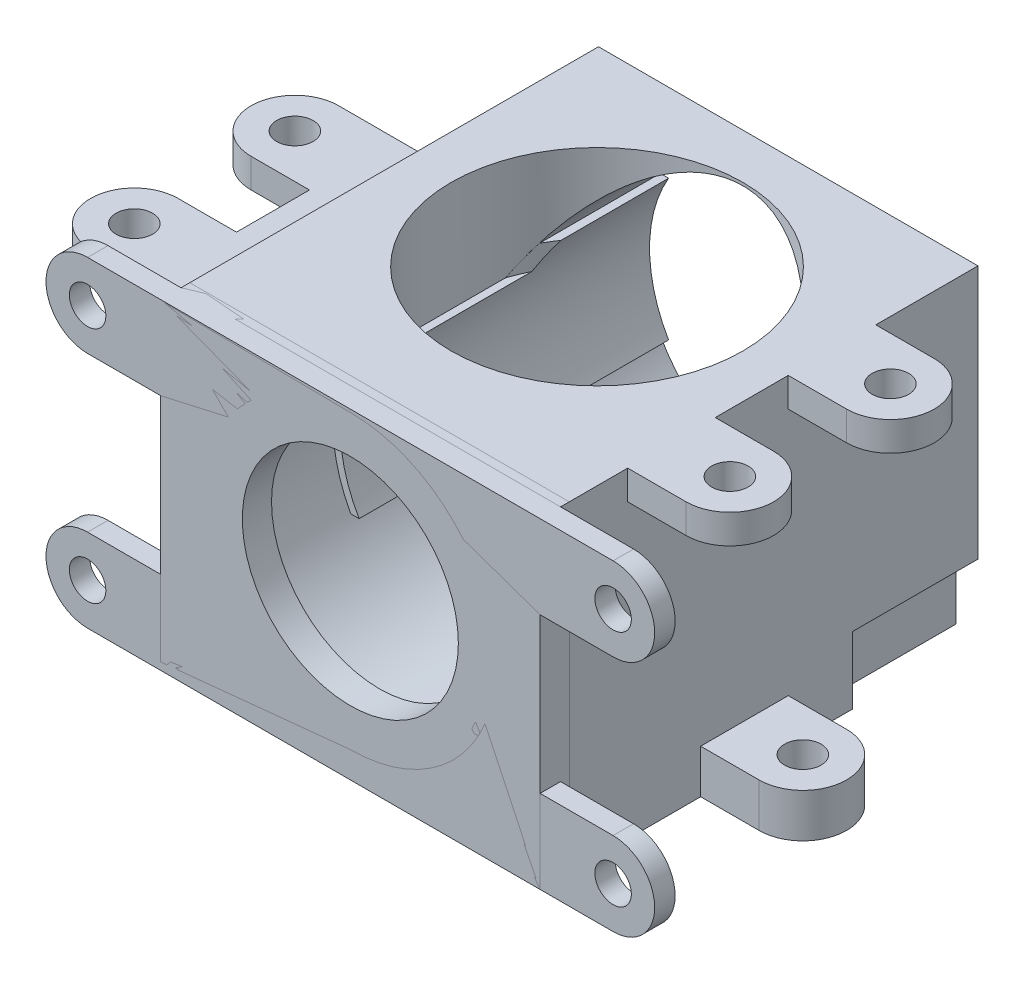
SolidWorks part; units mm, degrees
ref_plane "Front Plane" through (0, 0, 0) normal (0, 0, 1) x (1, 0, 0)
ref_plane "Top Plane" through (0, 0, 0) normal (0, 1, 0) x (1, 0, 0)
ref_plane "Right Plane" through (0, 0, 0) normal (1, 0, 0) x (0, 0, -1)
sketch "Sketch1" plane through (0, 0, 0) normal (0, 0, 1) x (1, 0, 0)
  line L1 (0, 0) -> (33.02, 0)
  line L2 (0, 0) -> (0, 27.94)
  line L3 (0, 27.94) -> (33.02, 27.94)
  line L4 (33.02, 0) -> (33.02, 27.94)
  dimension "D1" = 33.02
  dimension "D2" = 27.94
extrude "Boss-Extrude1" add sketch "Sketch1" along normal blind 38.1
sketch "Sketch2" plane through (0, 0, 38.1) normal (0, 0, 1) x (1, 0, 0)
  line L2 (0, 0) -> (33.02, 0) construction
  line L3 (33.02, 27.94) -> (0, 27.94) construction
  circle A1 centre (16.51, 14.986) radius 12.7
  point P10 (16.51, 0)
  dimension "D1" = 25.4
  dimension "D2" = 12.954
sketch "Sketch4" plane through (0, 27.94, 0) normal (0, 1, 0) x (1, 0, 0)
  line L0 (33.02, 0) -> (0, 0) construction
  line L1 (0, -38.1) -> (0, 0) construction
  circle A0 centre (16.51, -16.637) radius 12.7
  dimension "D1" = 25.4
  dimension "D2" = 16.637
  dimension "D3" = 16.51
extrude "Cut-Extrude3" cut sketch "Sketch4" against normal blind 14.224
ref_plane "Plane4" through (0, 3.81, 0) normal (0, -1, 0) x (-1, 0, 0)
sketch "Sketch3" plane through (0, 3.81, 0) normal (0, -1, 0) x (-1, 0, 0)
  line L0 (-33.02, 0) -> (0, 0) construction
  circle A1 centre (-16.51, -14.986) radius 5.715
  point P2 (-16.51, -16.637)
  point P6 (-16.51, 0)
  dimension "D1" = 11.43
  dimension "D2" = 14.986
extrude "Cut-Extrude4" cut sketch "Sketch3" along normal blind 2.032
sketch "Sketch7" plane through (0, 27.94, 0) normal (0, 1, 0) x (1, 0, 0)
  line L0 (33.02, -38.1) -> (33.02, 0) construction
  line L1 (33.02, -8.89) -> (38.1, -8.89)
  line L2 (33.02, -8.89) -> (33.02, -16.51)
  line L3 (33.02, -16.51) -> (38.1, -16.51)
  line L5 (33.02, 0) -> (0, 0) construction
  line L6 (33.02, -22.86) -> (38.1, -22.86)
  line L7 (33.02, -22.86) -> (33.02, -30.48)
  line L8 (33.02, -30.48) -> (38.1, -30.48)
  arc A0 (38.1, -30.48) -> (38.1, -22.86) centre (38.1, -26.67) ccw
  arc A1 (38.1, -8.89) -> (38.1, -16.51) centre (38.1, -12.7) cw
  circle A2 centre (38.1, -26.67) radius 1.5875
  circle A3 centre (38.1, -12.7) radius 1.5875
  dimension "D7" = 3.175
  dimension "D8" = 3.175
  dimension "D1" = 8.89
  dimension "D2" = 7.62
  dimension "D3" = 6.35
  dimension "D4" = 7.62
  dimension "D5" = 5.08
  dimension "D6" = 5.08
extrude "Boss-Extrude2" add sketch "Sketch7" against normal blind 2.54
sketch "Sketch9" plane through (0, 27.94, 0) normal (0, 1, 0) x (1, 0, 0)
  line L0 (0, -38.1) -> (0, 0) construction
  line L1 (-13.716, -8.89) -> (0, -8.89)
  line L3 (0, -8.89) -> (0, -30.48)
  line L5 (-8.636, -16.51) -> (-8.636, -22.86)
  line L14 (-13.716, -22.86) -> (-8.636, -22.86)
  line L15 (-8.636, -16.51) -> (-13.716, -16.51)
  line L18 (-13.716, -30.48) -> (0, -30.48)
  circle A8 centre (-13.716, -26.67) radius 1.5875
  arc A9 (-13.716, -30.48) -> (-13.716, -22.86) centre (-13.716, -26.67) cw
  arc A10 (-13.716, -16.51) -> (-13.716, -8.89) centre (-13.716, -12.7) cw
  circle A11 centre (-13.716, -12.7) radius 1.5875
  dimension "D2" = 3.81
  dimension "D3" = 3.175
  dimension "D5" = 3.81
  dimension "D6" = 3.175
  dimension "D7" = 13.716
  dimension "D1" = 13.716
extrude "Boss-Extrude4" add sketch "Sketch9" against normal blind 9.398
sketch "Sketch11" plane through (0, 0, 38.1) normal (0, 0, 1) x (1, 0, 0)
  line L3 (0, 21.082) -> (-23.9269, 21.082)
  line L5 (0, 21.082) -> (0, 27.94)
  line L6 (0, 27.94) -> (-23.9269, 27.94)
  line L7 (-23.9269, 27.94) -> (-23.9269, 21.082)
  dimension "D1" = 6.858
extrude "Cut-Extrude7" cut sketch "Sketch11" against normal through all
sketch "Sketch12" plane through (0, 0, 0) normal (0, 0, -1) x (-1, 0, 0)
  line L1 (-33.02, 0) -> (-31.115, 0)
  line L2 (-33.02, 0) -> (-33.02, 5.842)
  line L3 (-33.02, 5.842) -> (-31.115, 5.842)
  line L4 (-31.115, 0) -> (-31.115, 5.842)
  line L5 (0, 0) -> (-1.905, 0)
  line L6 (0, 0) -> (0, 5.842)
  line L7 (0, 5.842) -> (-1.905, 5.842)
  line L8 (-1.905, 0) -> (-1.905, 5.842)
  dimension "D1" = 1.905
  dimension "D2" = 5.842
  dimension "D3" = 5.842
extrude "Cut-Extrude8" cut sketch "Sketch12" against normal blind 10.922
extrude "Cut-Extrude12" cut sketch "Sketch2" against normal through all
sketch "Sketch14" plane through (0, 0, 38.1) normal (0, 0, 1) x (1, 0, 0)
  line L0 (5.3687, 21.082) -> (6.0983, 21.082)
  line L2 (16.51, 14.986) -> (16.51, 16.9303) construction
  line L4 (6.0983, 8.89) -> (5.3687, 8.89)
  line L5 (26.9217, 8.89) -> (27.6513, 8.89)
  line L6 (27.6513, 21.082) -> (26.9217, 21.082)
  arc A0 (6.0983, 21.082) -> (6.0983, 8.89) centre (16.51, 14.986) ccw
  circle A1 centre (16.51, 14.986) radius 12.7 construction
  arc A2 (5.3687, 21.082) -> (5.3687, 8.89) centre (16.51, 14.986) ccw
  arc A5 (27.6513, 21.082) -> (27.6513, 8.89) centre (16.51, 14.986) cw
  arc A6 (26.9217, 21.082) -> (26.9217, 8.89) centre (16.51, 14.986) cw
  dimension "D1" = 24.13
extrude "Boss-Extrude8" add sketch "Sketch14" against normal through all separate body
sketch "Sketch15" plane through (0, 0, 0) normal (0, -1, 0) x (1, 0, 0)
  line L1 (1.905, 0) -> (31.115, 0) construction
  line L17 (0, 24.13) -> (-5.08, 24.13)
  line L18 (-5.08, 16.51) -> (0, 16.51)
  line L22 (0, 16.51) -> (0, 24.13)
  line L23 (16.51, 0) -> (16.51, 8.9229) construction
  line L24 (33.02, 16.51) -> (33.02, 24.13)
  line L26 (38.1, 16.51) -> (33.02, 16.51)
  line L27 (33.02, 24.13) -> (38.1, 24.13)
  circle A0 centre (38.1, 20.32) radius 1.5875
  arc A1 (38.1, 16.51) -> (38.1, 24.13) centre (38.1, 20.32) ccw
  arc A10 (-5.08, 16.51) -> (-5.08, 24.13) centre (-5.08, 20.32) cw
  circle A11 centre (-5.08, 20.32) radius 1.5875
  dimension "D2" = 3.175
  dimension "D4" = 7.62
  dimension "D5" = 20.32
extrude "Boss-Extrude9" add sketch "Sketch15" against normal blind 3.81
sketch "Sketch16" plane through (0, 0, 38.1) normal (0, 0, 1) x (1, 0, 0)
  line L1 (0, 27.94) -> (0, 0) construction
  line L2 (-6.35, 27.94) -> (0, 27.94)
  line L3 (0, 27.94) -> (0, 20.701)
  line L4 (0, 20.701) -> (-6.35, 20.701)
  line L5 (-6.35, 7.239) -> (0, 7.239)
  line L6 (0, 7.239) -> (0, 0)
  line L7 (0, 0) -> (-6.35, 0)
  line L8 (16.51, 0) -> (16.51, 9.3518) construction
  line L9 (0, 0) -> (33.02, 0) construction
  line L10 (33.02, 0) -> (39.37, 0)
  line L11 (33.02, 7.239) -> (33.02, 0)
  line L12 (39.37, 7.239) -> (33.02, 7.239)
  line L13 (33.02, 20.701) -> (39.37, 20.701)
  line L14 (33.02, 27.94) -> (33.02, 20.701)
  line L15 (39.37, 27.94) -> (33.02, 27.94)
  circle A0 centre (-6.35, 24.3205) radius 1.5875
  arc A2 (-6.35, 20.701) -> (-6.35, 27.94) centre (-6.35, 24.3205) cw
  circle A3 centre (-6.35, 3.6195) radius 1.5875
  arc A4 (-6.35, 7.239) -> (-6.35, 0) centre (-6.35, 3.6195) ccw
  arc A5 (39.37, 7.239) -> (39.37, 0) centre (39.37, 3.6195) cw
  circle A6 centre (39.37, 3.6195) radius 1.5875
  arc A7 (39.37, 20.701) -> (39.37, 27.94) centre (39.37, 24.3205) ccw
  circle A8 centre (39.37, 24.3205) radius 1.5875
  dimension "D1" = 3.175
  dimension "D2" = 3.175
  dimension "D3" = 2.032
  dimension "D4" = 2.032
  dimension "D5" = 6.35
  dimension "D6" = 6.35
extrude "Boss-Extrude10" add sketch "Sketch16" against normal blind 1.778
sketch "Sketch17" plane through (0, 27.94, 0) normal (0, 1, 0) x (1, 0, 0)
  circle A0 centre (16.51, -16.637) radius 12.7
extrude "Cut-Extrude13" cut sketch "Sketch17" against normal blind 8.89
sketch "Sketch22" plane through (33.02, 0, 0) normal (1, 0, 0) x (0, 0, -1)
  line L0 (-22.86, 27.94) -> (-30.48, 27.94) construction
  line L1 (-38.1, 0) -> (-35.56, 0)
  line L2 (-38.1, 0) -> (-38.1, 27.94)
  line L3 (-38.1, 27.94) -> (-35.56, 27.94)
  line L4 (-35.56, 0) -> (-35.56, 27.94)
  dimension "D1" = 2.54
extrude "Boss-Extrude24" add sketch "Sketch22" against normal blind 33.02 separate body
sketch "Sketch23" plane through (0, 0, 38.1) normal (0, 0, 1) x (1, 0, 0)
  circle A0 centre (16.51, 14.986) radius 9.398
  dimension "D1" = 18.796
extrude "Cut-Extrude14" cut sketch "Sketch23" against normal blind 8.636
sketch "Sketch24" plane through (0, 0, 35.56) normal (0, 0, -1) x (-1, 0, 0)
  circle A0 centre (-16.51, 14.986) radius 12.7
extrude "Cut-Extrude15" cut sketch "Sketch24" along normal blind 8.636
